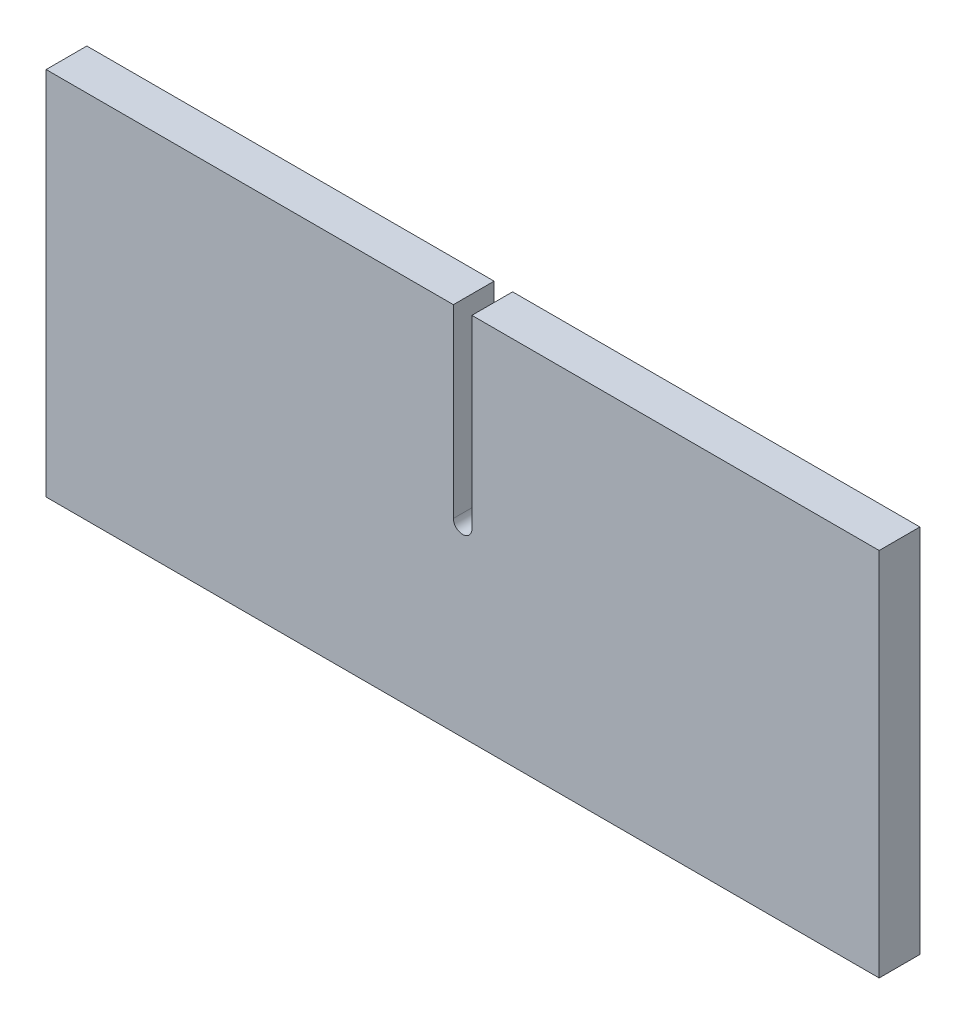
SolidWorks part; units mm, degrees
ref_plane "Front Plane" through (0, 0, 0) normal (0, 0, 1) x (1, 0, 0)
ref_plane "Top Plane" through (0, 0, 0) normal (0, 1, 0) x (1, 0, 0)
ref_plane "Right Plane" through (0, 0, 0) normal (1, 0, 0) x (0, 0, -1)
sketch "Sketch1" plane through (0, 0, 0) normal (0, 0, 1) x (1, 0, 0)
  line L0 (5, 100) -> (5, 0)
  line L1 (-225, 100) -> (-5, 100)
  line L2 (-225, 100) -> (-225, -100)
  line L3 (-225, -100) -> (225, -100)
  line L4 (225, 100) -> (225, -100)
  line L5 (-225, 100) -> (225, -100) construction
  line L6 (-225, -100) -> (225, 100) construction
  line L7 (-5, 100) -> (-5, 0)
  line L8 (5, 0) -> (-5, 0) construction
  line L9 (5, 100) -> (225, 100)
  arc A0 (-5, 0) -> (5, 0) centre (0, 0) ccw
  point P0 (0, 0)
  dimension "D1" = 450
  dimension "D2" = 200
  dimension "D3" = 100
  dimension "D4" = 100
  dimension "D6" = 220
extrude "Boss-Extrude1" add sketch "Sketch1" along normal blind 22
